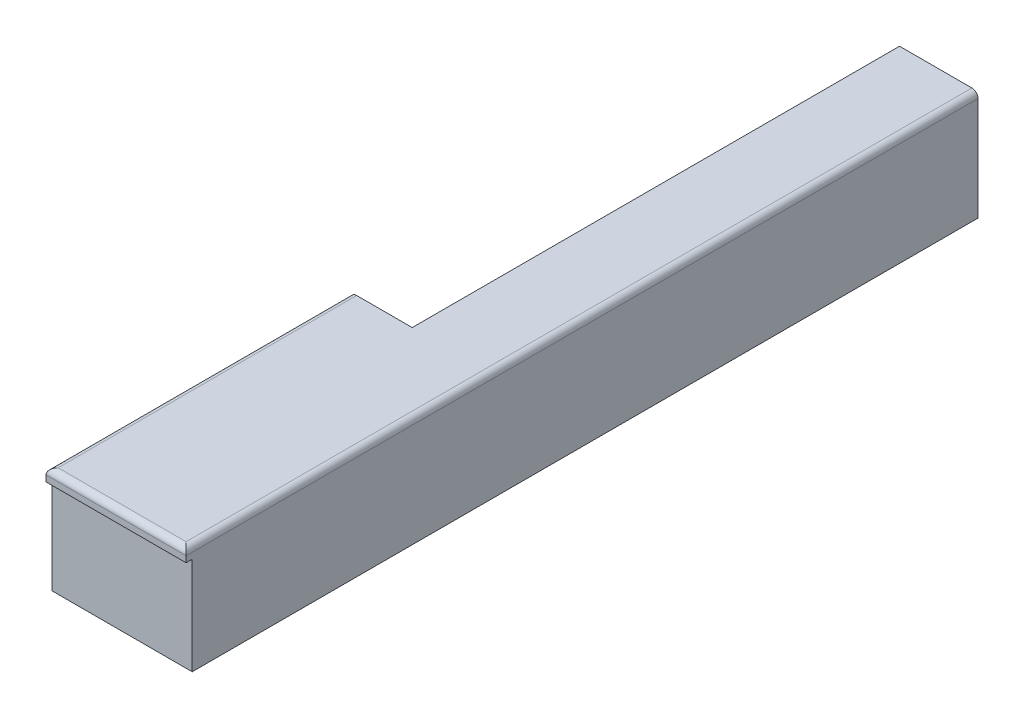
SolidWorks part; units mm, degrees
material "Pino"
ref_plane "Alzado" through (0, 0, 0) normal (0, 0, 1) x (1, 0, 0)
ref_plane "Planta" through (0, 0, 0) normal (0, 1, 0) x (1, 0, 0)
ref_plane "Vista lateral" through (0, 0, 0) normal (1, 0, 0) x (0, 0, -1)
sketch "Croquis2" plane through (0, 0, 0) normal (0, 1, 0) x (1, 0, 0)
  line L1 (0, 0) -> (23, 0)
  line L2 (0, 0) -> (0, 130)
  line L3 (0, 130) -> (23, 130)
  line L4 (23, 0) -> (23, 130)
  line L5 (0, 130) -> (10.12, 130)
  line L6 (0, 115.866) -> (0, 50)
  line L7 (23, 50) -> (20, 50)
  line L9 (0, 50) -> (10.12, 50)
  line L10 (0, 130) -> (0, 50)
  line L11 (0, 50) -> (10.12, 50)
  line L12 (10.12, 130) -> (10.12, 50)
  dimension "D1" = 23
  dimension "D2" = 130
  dimension "D3" = 50
  dimension "D4" = 12.88
  dimension "D5" = 10.12
extrude "Saliente-Extruir1" add sketch "Croquis2" along normal blind 18
sketch "Croquis4" plane through (0, 0, 0) normal (0, 0, 1) x (1, 0, 0)
  line L0 (23, 18) -> (23, 0) construction
  line L1 (0, 0) -> (23, 0)
  line L2 (0, 0) -> (0, 16)
  line L3 (0, 16) -> (23, 16)
  line L4 (23, 0) -> (23, 16)
  dimension "D1" = 16
extrude "Cortar-Extruir1" cut sketch "Croquis4" against normal blind 1
fillet "Redondeo1" radius 1 3 edges at (11.5, 18, 0) (23, 18, -65) (0, 18, -25)
